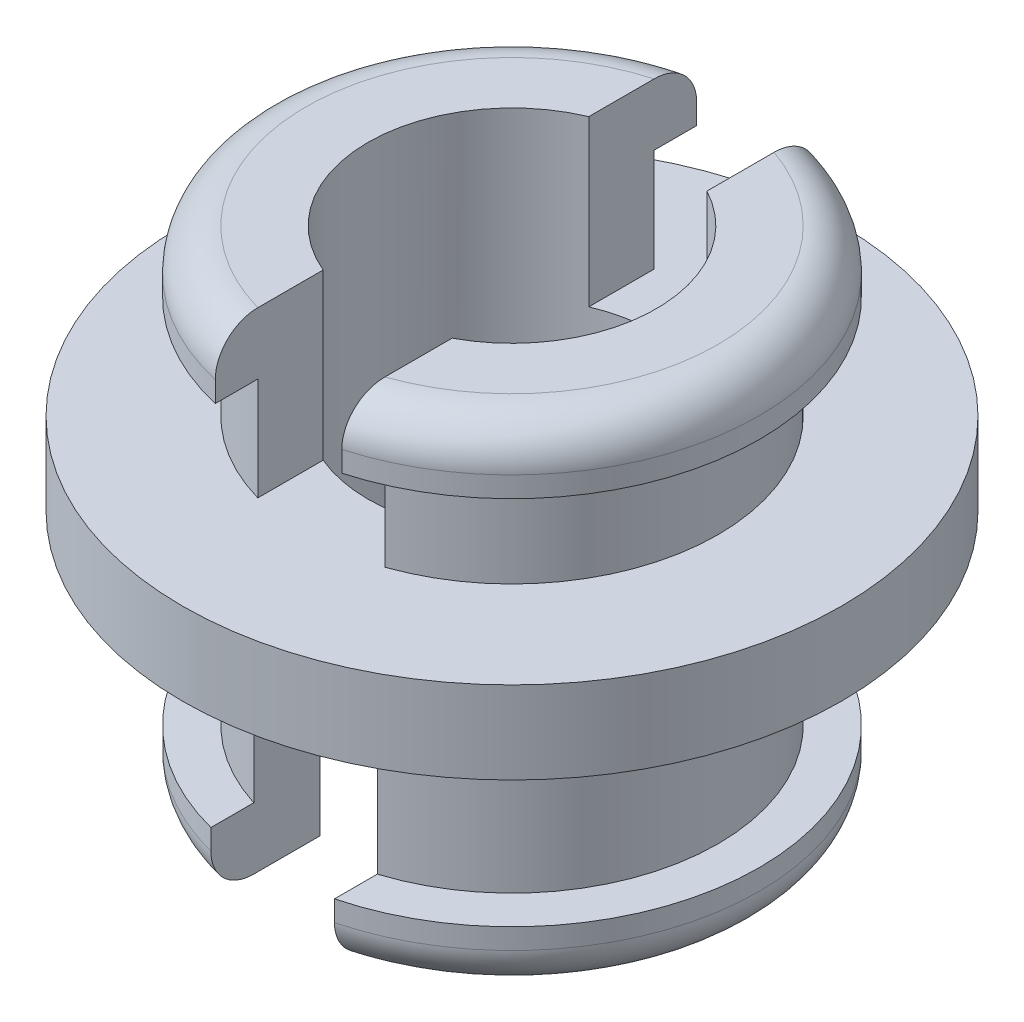
SolidWorks part; units mm, degrees
ref_plane "Plan de face" through (0, 0, 0) normal (0, 0, 1) x (1, 0, 0)
ref_plane "Plan de dessus" through (0, 0, 0) normal (0, 1, 0) x (1, 0, 0)
ref_plane "Plan de droite" through (0, 0, 0) normal (1, 0, 0) x (0, 0, -1)
sketch "Esquisse1" plane through (0, 0, 0) normal (0, 0, 1) x (1, 0, 0)
  line L0 (0, 12) -> (0, 78.7522) construction
  line L1 (-5, 1.5) -> (-5, 6)
  line L2 (-5, 6) -> (-8, 6)
  line L3 (-8, 6) -> (-8, 8)
  line L4 (-8, 8) -> (-5, 8)
  line L5 (-5, 8) -> (-5, 10.5)
  line L6 (-5, 12) -> (-3.5, 12)
  line L8 (-3.5, 0) -> (-5, 0)
  line L9 (-3.5, 12) -> (-3.5, 0)
  line L10 (-5, 10.5) -> (-6, 10.5)
  line L13 (-6, 10.5) -> (-6, 11)
  line L16 (-5, 1.5) -> (-6, 1.5)
  line L17 (-6, 1) -> (-6, 1.5)
  arc A0 (-5, 12) -> (-6, 11) centre (-5, 11) ccw
  arc A1 (-5, 0) -> (-6, 1) centre (-5, 1) cw
  point P7 (-5, 10.5)
  point P11 (-5, 1.5)
  dimension "D11" = 1
  dimension "D2" = 5
  dimension "D3" = 2
  dimension "D4" = 8
  dimension "D5" = 5
  dimension "D8" = 1
  dimension "D10" = 1
  dimension "D12" = 3.5
revolve "Révolution2" add sketch "Esquisse1" angle 360 about L0
sketch "Esquisse2" plane through (0, 12, 0) normal (0, 1, 0) x (1, 0, 0)
  line L0 (1.6395, 6.5045) -> (1.6395, -6.5045)
  line L1 (1.6395, 6.5045) -> (-1.3605, 6.5045)
  line L3 (1.6395, -6.5045) -> (-1.3605, -6.5045)
  line L4 (-1.3605, 6.5045) -> (-1.3605, -6.5045)
  dimension "D1" = 3
extrude "Enlèv. mat.-Extru.1" cut sketch "Esquisse2" against normal blind 4
sketch "Esquisse3" plane through (0, 0, 0) normal (0, -1, 0) x (1, 0, 0)
  line L0 (1.5, 6.5641) -> (1.5, -6.5641)
  line L1 (1.5, 6.5641) -> (-1.5, 6.5641)
  line L3 (1.5, -6.5641) -> (-1.5, -6.5641)
  line L4 (-1.5, 6.5641) -> (-1.5, -6.5641)
  dimension "D1" = 3
extrude "Enlèv. mat.-Extru.2" cut sketch "Esquisse3" against normal blind 6
